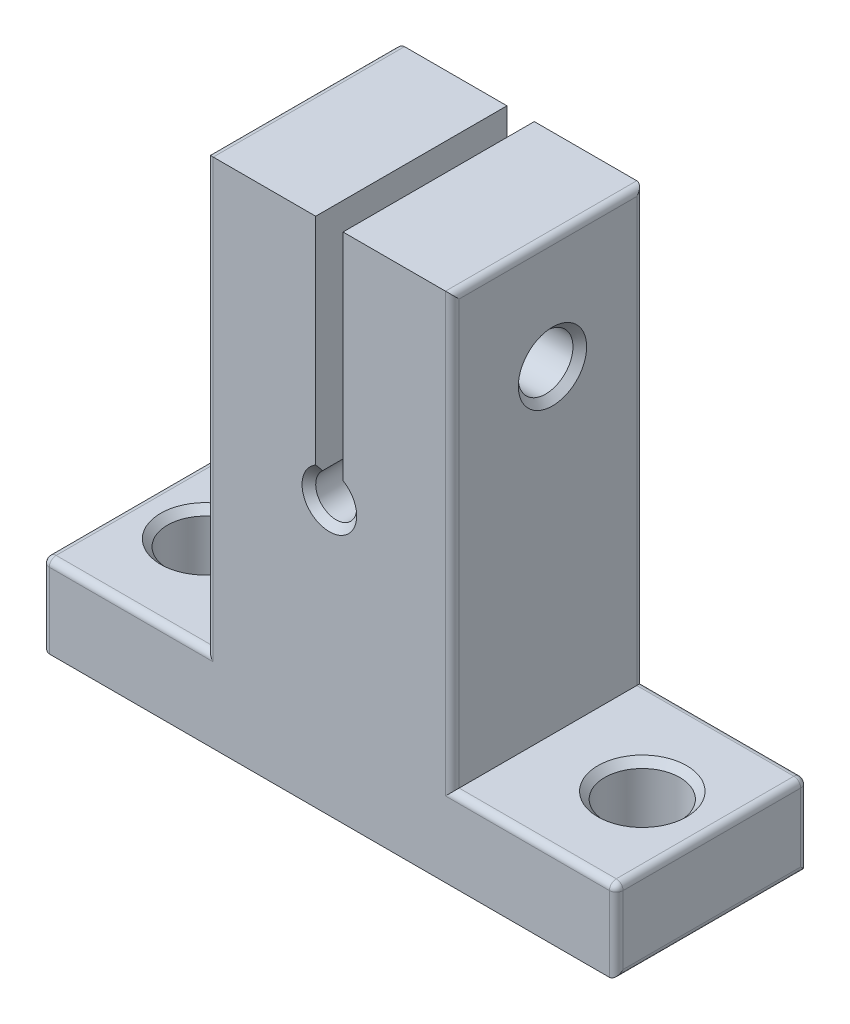
SolidWorks part; units mm, degrees
material "1060 Alloy"
ref_plane "Front Plane" through (0, 0, 0) normal (0, 0, 1) x (1, 0, 0)
ref_plane "Top Plane" through (0, 0, 0) normal (0, 1, 0) x (1, 0, 0)
ref_plane "Right Plane" through (0, 0, 0) normal (1, 0, 0) x (0, 0, -1)
sketch "Sketch1" plane through (0, 0, 0) normal (0, 0, 1) x (1, 0, 0)
  line L0 (0, 0) -> (-50000, 0) construction
  line L1 (0, 0) -> (0, 50000) construction
  line L2 (-21, -3) -> (-21, 3)
  line L3 (-21, 3) -> (-9, 3)
  line L4 (-9, 3) -> (-9, 34.5)
  line L5 (-9, 34.5) -> (-1, 34.5)
  line L6 (9, 34.5) -> (9, 3)
  line L7 (9, 3) -> (21, 3)
  line L8 (21, 3) -> (21, -3)
  line L9 (21, -3) -> (-21, -3)
  line L10 (16, -3) -> (16, 3) construction
  line L11 (-16, -3) -> (-16, 3) construction
  line L12 (-1, 34.5) -> (-1, 18.118)
  line L13 (1, 34.5) -> (1, 18.118)
  line L14 (1, 34.5) -> (9, 34.5)
  arc A0 (-1, 18.118) -> (1, 18.118) centre (0, 17) ccw
  point P8 (-21, 0)
  point P15 (0, -3)
  point P21 (16, 0)
  dimension "Shaft Diameter" = 3
  dimension "W" = 42
  dimension "P" = 18
  dimension "F" = 37.5
  dimension "G" = 6
  dimension "B" = 32
  dimension "D1" = 2
  dimension "h" = 20
extrude "Boss-Extrude1" add sketch "Sketch1" along normal mid plane 14
sketch "Sketch2" plane through (0, 3, 0) normal (0, 1, 0) x (1, 0, 0)
  line L0 (0, 0) -> (50000, 0) construction
  line L1 (0.3141, 0) -> (-49999.6859, 0) construction
  line L2 (-0.0955, 2.4842) -> (-0.0955, 50002.4842) construction
  circle A0 centre (15.9045, 0) radius 2.75
  circle A1 centre (-16.0955, 0) radius 2.75
  dimension "B" = 32
  dimension "S" = 5.5
extrude "Cut-Extrude1" cut sketch "Sketch2" against normal through all
sketch "Sketch5" plane through (-1, 0, 0) normal (1, 0, 0) x (0, 0, -1)
  line L0 (-7, 26.309) -> (7, 26.309) construction
  line L1 (7, 18.118) -> (7, 34.5) construction
  line L2 (0, 34.5) -> (0, 18.118) construction
  line L3 (-7, 34.5) -> (7, 34.5) construction
  line L4 (-7, 18.118) -> (7, 18.118) construction
  line L5 (-7, 18.118) -> (-7, 34.5) construction
  circle A0 centre (0.3307, 26.309) radius 2
  dimension "Clamping bold" = 4
extrude "Cut-Extrude2" cut sketch "Sketch5" against normal through all both and the other way through all
chamfer "Chamfer2" distance 0.5 angle 45 6 edges at (0, 15.5, -7) (0, 15.5, 7) (-9, 26.309, -2.3307) (-13.3455, 3, 0) (9, 26.309, 1.6693) (13.1545, 3, 0)
fillet "Fillet2" radius 0.5 18 edges at (21, -3, 0) (21, 0, 7) (21, 3, 0) (21, 0, -7) (-21, 3, 0) (-21, 0, 7) (-21, -3, 0) (-21, 0, -7) (-15, 3, -7) (-15, 3, 7) (-9, 18.75, 7) (-9, 34.5, 0) (-9, 18.75, -7) (9, 18.75, -7) (9, 18.75, 7) (15, 3, 7) (15, 3, -7) (9, 34.5, 0)
equation "\"W\"= \"W@Sketch1\"'Width"
equation "\"B\"= \"B@Sketch1\"'between hold"
equation "\"F\"= \"F@Sketch1\"'Hight"
equation "\"P\"= \"P@Sketch1\""
equation "\"G\"= \"G@Sketch1\""
equation "\"Shaft diameter\"= \"Shaft Diameter@Sketch1\""
equation "\"S\"= 5.5'M5"
equation "\"Clamping bold\"= 4'M4"
equation "\"h\"= \"h@Sketch1\""
